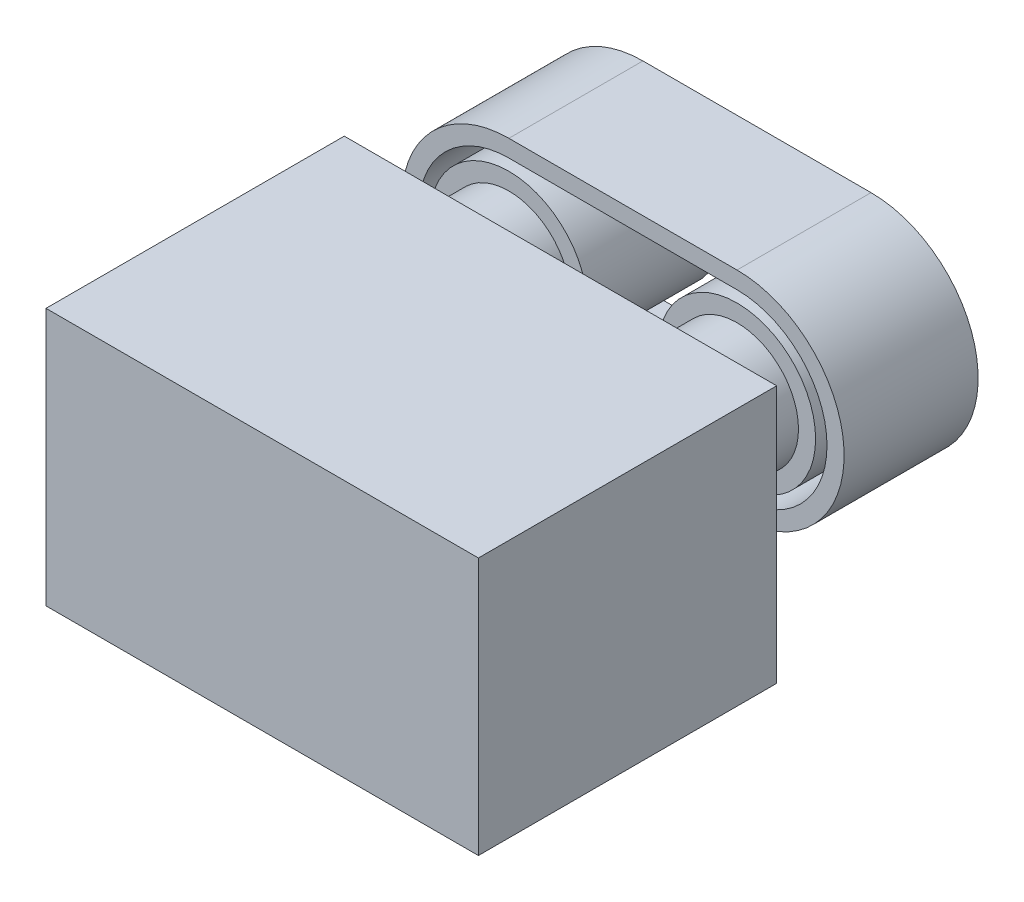
SolidWorks part; units mm, degrees
ref_plane "前视基准面" through (0, 0, 0) normal (0, 0, 1) x (1, 0, 0)
ref_plane "上视基准面" through (0, 0, 0) normal (0, 1, 0) x (1, 0, 0)
ref_plane "右视基准面" through (0, 0, 0) normal (1, 0, 0) x (0, 0, -1)
sketch "草图1" plane through (0, 0, 0) normal (0, 0, 1) x (1, 0, 0)
  line L0 (189.609, 0) -> (-173.0388, 0) construction
  circle A1 centre (-73.6191, 0) radius 35
  circle A2 centre (27.9809, 0) radius 35
  circle A3 centre (129.5809, 0) radius 35
  dimension "D1" = 70
  dimension "D2" = 101.6
  dimension "D3" = 101.6
extrude "凸台-拉伸1" add sketch "草图1" along normal blind 59.69
ref_plane "基准面1" through (0, 0, 29.845) normal (0, 0, 1) x (1, 0, 0)
sketch "草图2" plane through (0, 0, 29.845) normal (0, 0, 1) x (1, 0, 0)
  line L0 (27.9809, 47.7) -> (129.5809, 47.7)
  line L1 (27.9809, -47.7) -> (129.5809, -47.7)
  line L2 (27.9809, 40.08) -> (129.5809, 40.08)
  line L3 (27.9809, -40.08) -> (129.5809, -40.08)
  arc A0 (27.9809, 40.08) -> (27.9809, -40.08) centre (27.9809, 0) ccw
  arc A1 (27.9809, 47.7) -> (27.9809, -47.7) centre (27.9809, 0) ccw
  circle A5 centre (129.5809, 0) radius 47.7
  arc A6 (129.5809, -47.7) -> (129.5809, 47.7) centre (129.5809, 0) ccw
  arc A8 (129.5809, -40.08) -> (129.5809, 40.08) centre (129.5809, 0) ccw
  circle A10 centre (129.5809, 0) radius 47.7 construction
  circle A13 centre (129.5809, 0) radius 40.08 construction
  point P4 (-73.6191, 0)
  point P9 (-28.0033, 13.9461)
  point P10 (-73.6191, 0)
  point P11 (169.6609, 0)
  point P12 (175.1967, 13.9461)
  point P20 (-33.5391, 0)
  dimension "D2" = 12.7
  dimension "D4" = 7.62
extrude "凸台-拉伸2" add sketch "草图2" along normal mid plane 59.69 separate body
sketch "草图3" plane through (0, 0, 59.69) normal (0, 0, 1) x (1, 0, 0)
  circle A2 centre (-73.6191, 0) radius 27.38
  circle A3 centre (-73.6191, 0) radius 27.38
  circle A9 centre (27.9809, 0) radius 27.38
  circle A10 centre (27.9809, 0) radius 27.38
  circle A12 centre (129.5809, 0) radius 27.38
  circle A13 centre (129.5809, 0) radius 27.38
  dimension "D1" = 7.62
  dimension "D2" = 7.62
  dimension "D3" = 7.62
extrude "凸台-拉伸3" add sketch "草图3" along normal blind 20.32 contours A13 | A3 | A10
sketch "草图4" plane through (0, 0, 80.01) normal (0, 0, 1) x (1, 0, 0)
  line L2 (-112.0934, 0) -> (-112.0934, -82.5676)
  line L3 (-112.0934, -82.5676) -> (167.571, -82.5676)
  line L4 (167.571, 0) -> (167.571, -82.5676)
  line L6 (167.571, 0) -> (167.571, 32.2038)
  line L7 (167.571, 32.2038) -> (-112.0934, 32.2038)
  line L8 (-112.0934, 0) -> (-112.0934, 32.2038)
  point P6 (0, 0)
extrude "凸台-拉伸4" add sketch "草图4" along normal blind 132.842
sketch "草图5" plane through (0, 0, 0) normal (0, 0, -1) x (-1, 0, 0)
  circle A1 centre (73.6191, 0) radius 35
  circle A2 centre (73.6191, 0) radius 35
  dimension "D1" = 0
extrude "切除-拉伸1" cut sketch "草图5" against normal up to surface (80.01 mm away) up to face at (156.9609, 0, 80.01)
sketch "草图6" plane through (0, 0, 80.01) normal (0, 0, -1) x (-1, 0, 0)
  line L1 (25.0135, 53.1967) -> (144.217, 53.1967)
  line L2 (25.0135, 53.1967) -> (25.0135, -112.2335)
  line L3 (25.0135, -112.2335) -> (144.217, -112.2335)
  line L4 (144.217, 53.1967) -> (144.217, -112.2335)
extrude "切除-拉伸2" cut sketch "草图6" against normal blind 171.704
